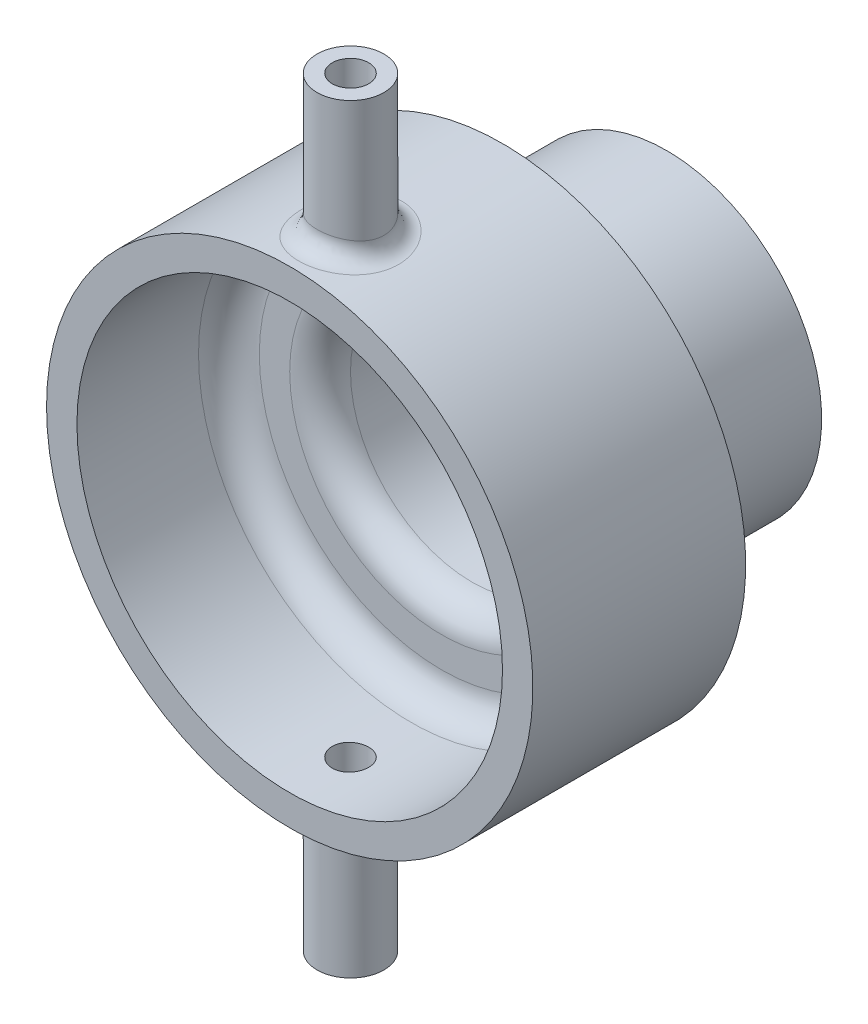
SolidWorks part; units mm, degrees
ref_plane "Front Plane" through (0, 0, 0) normal (0, 0, 1) x (1, 0, 0)
ref_plane "Top Plane" through (0, 0, 0) normal (0, 1, 0) x (1, 0, 0)
ref_plane "Right Plane" through (0, 0, 0) normal (1, 0, 0) x (0, 0, -1)
sketch "Sketch1" plane through (0, 0, 0) normal (0, 1, 0) x (1, 0, 0)
  line L0 (0, 0) -> (40, 0)
  line L1 (40, 0) -> (40, 35)
  line L2 (40, 35) -> (25.5, 35)
  line L3 (25.5, 35) -> (25.5, 62)
  line L4 (25.5, 62) -> (0, 62)
  line L5 (0, 62) -> (0, 0)
  dimension "D1" = 35
  dimension "D2" = 27
  dimension "D3" = 25.5
  dimension "D4" = 40
revolve "Revolve1" add sketch "Sketch1" angle 360 about L5
chamfer "Chamfer1" distance 10 angle 45 1 edges at (-25.5, 0, -35)
sketch "Sketch2" plane through (0, 0, -62) normal (0, 0, -1) x (-1, 0, 0)
  circle A0 centre (0, 0) radius 1.25
  dimension "D1" = 2.5
extrude "Cut-Extrude1" cut sketch "Sketch2" against normal blind 30
sketch "Sketch5" plane through (0, 0, 0) normal (0, 1, 0) x (1, 0, 0)
  circle A0 centre (0, 10) radius 5.5
  dimension "D1" = 11
  dimension "D2" = 10
extrude "Boss-Extrude1" add sketch "Sketch5" along normal mid plane 125
sketch "Sketch3" plane through (0, 0, 0) normal (0, 0, 1) x (1, 0, 0)
  circle A0 centre (0, 0) radius 35
  dimension "D1" = 70
extrude "Cut-Extrude2" cut sketch "Sketch3" against normal blind 25
sketch "Sketch4" plane through (0, 0, -25) normal (0, 0, 1) x (1, 0, 0)
  circle A0 centre (0, 0) radius 20
  dimension "D1" = 40
extrude "Cut-Extrude3" cut sketch "Sketch4" against normal offset from surface (32 mm away) 5 up to face at (-1.25, 0, -62)
fillet "Fillet1" radius 5 3 edges at (20, 0, -25) (20, 0, -57) (35, 0, -25)
fillet "Fillet2" radius 3 2 edges at (-1.2068, -39.9818, -4.634) (1.2068, 39.9818, -4.634)
sketch "Sketch6" plane through (0, 62.5, 0) normal (0, 1, 0) x (1, 0, 0)
  circle A0 centre (0, 10) radius 3
  dimension "D1" = 6
extrude "Cut-Extrude4" cut sketch "Sketch6" against normal through all
